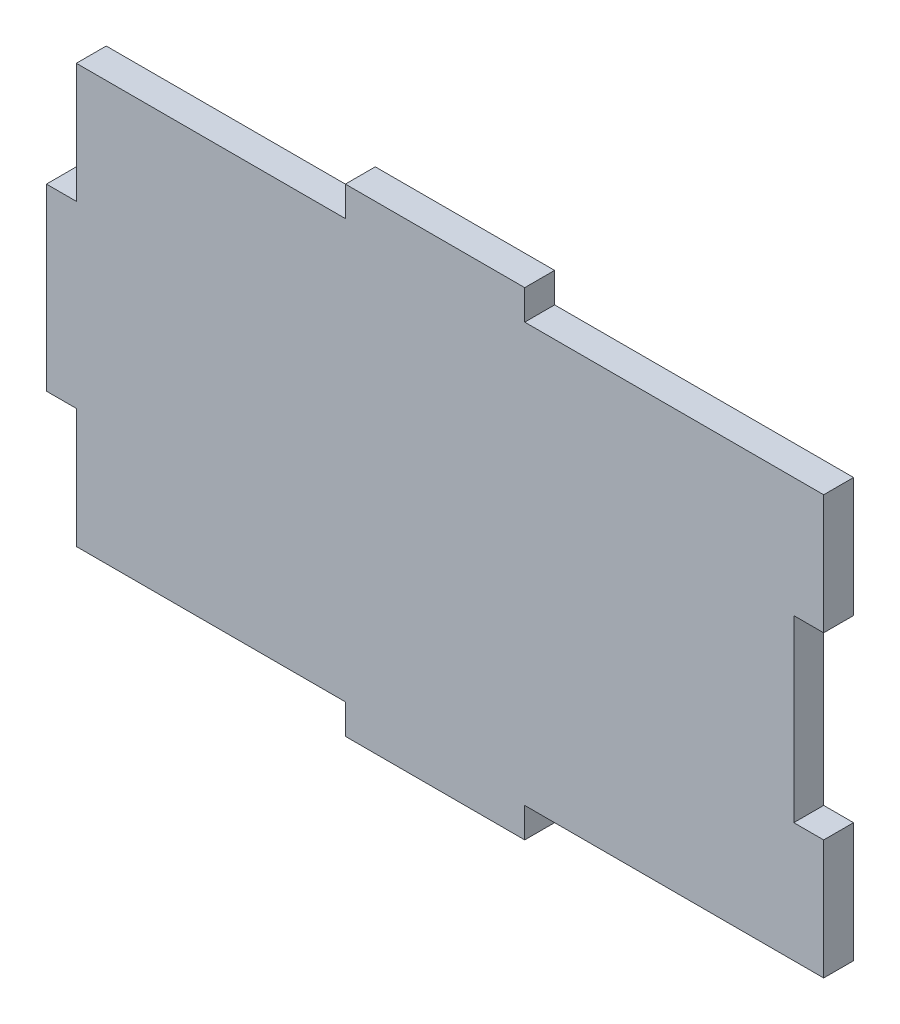
SolidWorks part; units mm, degrees
ref_plane "Front Plane" through (0, 0, 0) normal (0, 0, 1) x (1, 0, 0)
ref_plane "Top Plane" through (0, 0, 0) normal (0, 1, 0) x (1, 0, 0)
ref_plane "Right Plane" through (0, 0, 0) normal (1, 0, 0) x (0, 0, -1)
sketch "Sketch1" plane through (0, 0, 0) normal (0, 0, 1) x (1, 0, 0)
  line L1 (0, 0) -> (79.375, 0)
  line L2 (0, 0) -> (0, 44.45)
  line L3 (0, 44.45) -> (79.375, 44.45)
  line L4 (79.375, 0) -> (79.375, 44.45)
  dimension "D1" = 44.45
  dimension "D2" = 79.375
extrude "Boss-Extrude1" add sketch "Sketch1" along normal blind 3.175
sketch "Sketch2" plane through (0, 0, 3.175) normal (0, 0, 1) x (1, 0, 0)
  line L0 (0, -55) -> (0, 55) construction
  line L1 (0, 31.75) -> (-3.175, 31.75)
  line L2 (0, 31.75) -> (0, 12.7)
  line L3 (0, 12.7) -> (-3.175, 12.7)
  line L4 (-3.175, 31.75) -> (-3.175, 12.7)
  line L5 (79.375, 44.45) -> (0, 44.45) construction
  dimension "D1" = 3.175
  dimension "D2" = 19.05
  dimension "D3" = 12.7
extrude "Boss-Extrude2" add sketch "Sketch2" against normal blind 3.175
sketch "Sketch5" plane through (0, 0, 3.175) normal (0, 0, 1) x (1, 0, 0)
  line L0 (79.375, 44.45) -> (0, 44.45) construction
  line L1 (28.575, 44.45) -> (47.625, 44.45)
  line L2 (28.575, 44.45) -> (28.575, 47.625)
  line L3 (28.575, 47.625) -> (47.625, 47.625)
  line L4 (47.625, 44.45) -> (47.625, 47.625)
  line L6 (-3.175, 22.225) -> (79.375, 22.225) construction
  line L7 (47.625, 0) -> (47.625, -3.175)
  line L8 (28.575, -3.175) -> (47.625, -3.175)
  line L9 (28.575, 0) -> (28.575, -3.175)
  line L10 (28.575, 0) -> (47.625, 0)
  line L13 (-3.175, 31.75) -> (-3.175, 12.7) construction
  line L14 (79.375, 0) -> (79.375, 44.45) construction
  point P12 (38.1, 0)
  point P18 (38.1, 22.225)
  point P19 (38.1, 44.45)
  dimension "D1" = 19.05
  dimension "D2" = 3.175
extrude "Boss-Extrude3" add sketch "Sketch5" against normal blind 3.175
sketch "Sketch3" plane through (0, 0, 3.175) normal (0, 0, 1) x (1, 0, 0)
  line L0 (79.375, 0) -> (79.375, 44.45) construction
  line L1 (79.375, 12.7) -> (76.2, 12.7)
  line L2 (79.375, 12.7) -> (79.375, 31.75)
  line L3 (79.375, 31.75) -> (76.2, 31.75)
  line L4 (76.2, 12.7) -> (76.2, 31.75)
  line L5 (79.375, 44.45) -> (47.625, 44.45) construction
  dimension "D1" = 19.05
  dimension "D2" = 3.175
  dimension "D3" = 12.7
extrude "Cut-Extrude1" cut sketch "Sketch3" against normal blind 3.175
